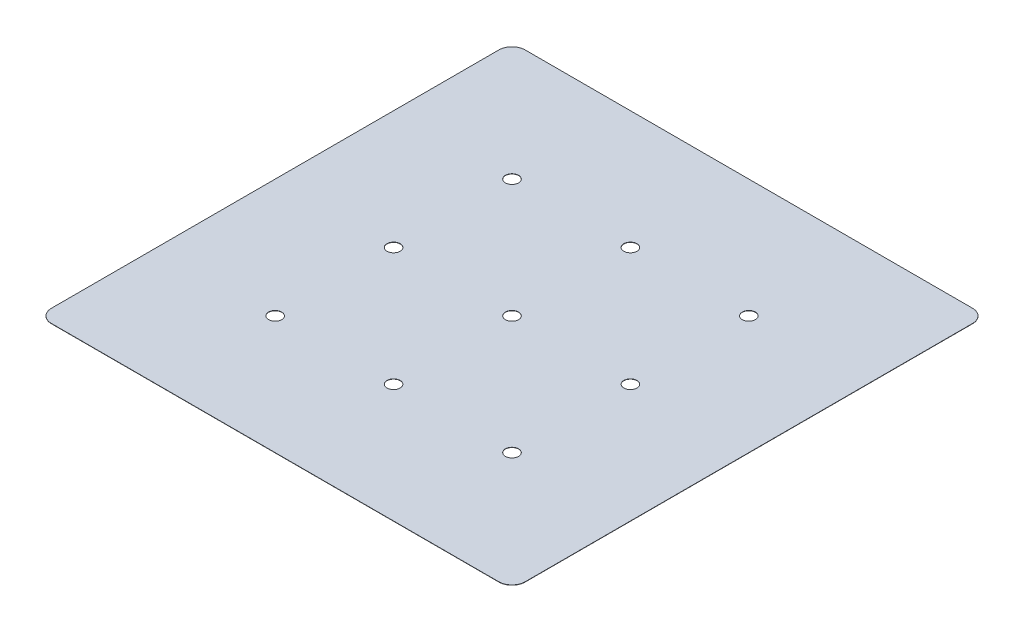
SolidWorks part; units mm, degrees
ref_plane "Front Plane" through (0, 0, 0) normal (0, 0, 1) x (1, 0, 0)
ref_plane "Top Plane" through (0, 0, 0) normal (0, 1, 0) x (1, 0, 0)
ref_plane "Right Plane" through (0, 0, 0) normal (1, 0, 0) x (0, 0, -1)
sketch "Sketch1" plane through (0, 0, 0) normal (0, 1, 0) x (1, 0, 0)
  line L0 (-90, 180) -> (-90, -180)
  line L1 (-170, 180) -> (170, 180)
  line L2 (-180, 170) -> (-180, -170)
  line L3 (-170, -180) -> (170, -180)
  line L4 (180, 170) -> (180, -170)
  line L5 (-180, 180) -> (180, -180) construction
  line L6 (-180, -180) -> (180, 180) construction
  line L7 (0, 180) -> (0, -180)
  line L8 (90, 180) -> (90, -180)
  line L9 (-180, -90) -> (180, -90)
  line L10 (-180, 0) -> (180, 0)
  line L11 (-180, 90) -> (180, 90)
  circle A0 centre (-90, 90) radius 5
  circle A1 centre (-90, 0) radius 5
  circle A2 centre (-90, -90) radius 5
  circle A3 centre (0, -90) radius 5
  circle A4 centre (0, 0) radius 5
  circle A5 centre (0, 90) radius 5
  circle A6 centre (90, 90) radius 5
  circle A7 centre (90, 0) radius 5
  circle A8 centre (90, -90) radius 5
  arc A9 (-180, -170) -> (-170, -180) centre (-170, -170) ccw
  arc A10 (170, -180) -> (180, -170) centre (170, -170) ccw
  arc A11 (170, 180) -> (180, 170) centre (170, 170) cw
  arc A12 (-170, 180) -> (-180, 170) centre (-170, 170) ccw
  point P0 (0, 0)
  point P36 (0, 0)
  point P37 (0, 0)
  point P38 (0, 0)
  point P39 (0, 0)
  point P40 (0, 0)
  point P41 (0, 0)
  dimension "D4" = 10
  dimension "D5" = 10
  dimension "D1" = 360
  dimension "D2" = 90
  dimension "D3" = 90
extrude "Boss-Extrude1" add sketch "Sketch1" along normal blind 0.2 contours L1 A12 L2 L11 A0 L0 | A5 L7 L1 L0 A0 L11 | A5 L11 A0 L0 A1 L10 A4 L7 | A1 L0 A0 L11 L2 L10 | A2 L0 A1 L10 L2 L9 | L2 A9 L3 L0 A2 L9 | A3 L9 A2 L0 L3 L7 | A4 L10 A1 L0 A2 L9 A3 L7 | A8 L8 A7 L10 A4 L7 A3 L9 | A8 L9 A3 L7 L3 L8 | L3 A10 L4 L9 A8 L8 | A8 L9 L4 L10 A7 L8 | A7 L8 A6 L11 A5 L7 A4 L10 | A7 L10 L4 L11 A6 L8 | A11 L1 L8 A6 L11 L4 | A6 L8 L1 L7 A5 L11
